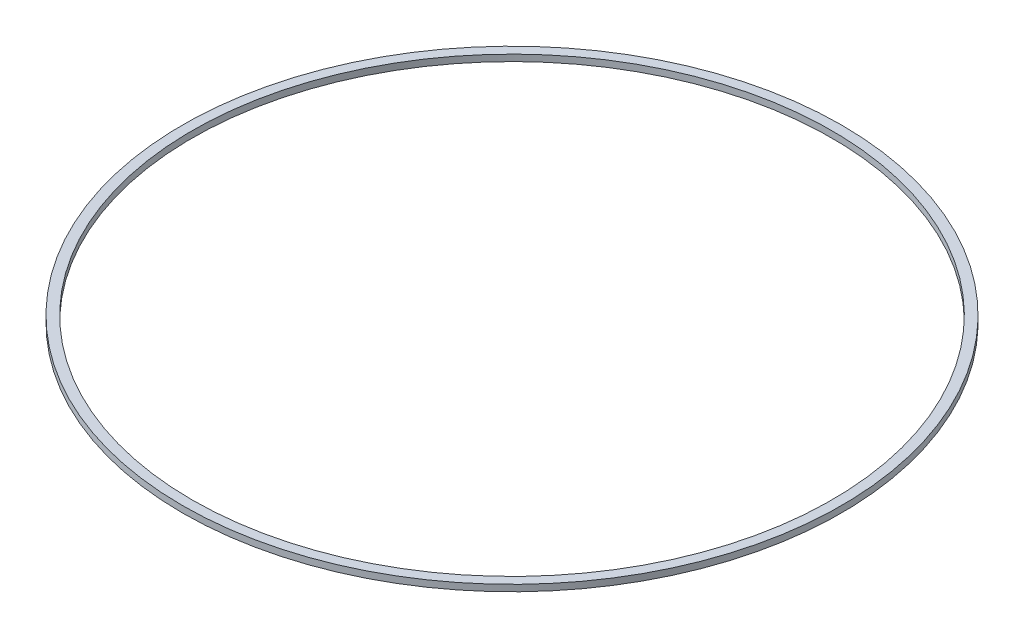
SolidWorks part; units mm, degrees
ref_plane "Front Plane" through (0, 0, 0) normal (0, 0, 1) x (1, 0, 0)
ref_plane "Top Plane" through (0, 0, 0) normal (0, 1, 0) x (1, 0, 0)
ref_plane "Right Plane" through (0, 0, 0) normal (1, 0, 0) x (0, 0, -1)
sketch "Sketch1" plane through (0, 0, 0) normal (0, 1, 0) x (1, 0, 0)
  circle A0 centre (0, 0) radius 98.9
  circle A1 centre (0, 0) radius 101.9
  dimension "D1" = 3
  dimension "D2" = 203.8
  dimension "D3" = 197.8
extrude "Boss-Extrude1" add sketch "Sketch1" along normal blind 2
